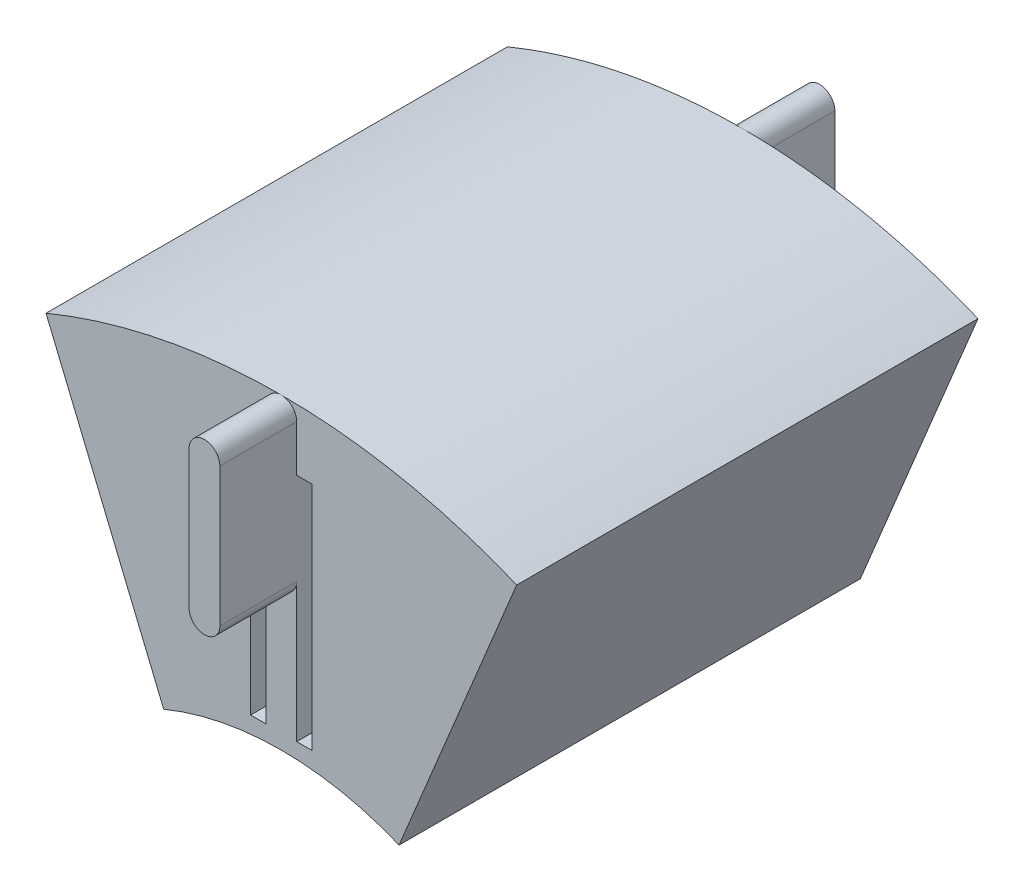
SolidWorks part; units mm, degrees
ref_plane "Ön Düzlem" through (0, 0, 0) normal (0, 0, 1) x (1, 0, 0)
ref_plane "Üst Düzlem" through (0, 0, 0) normal (0, 1, 0) x (1, 0, 0)
ref_plane "Sağ Düzlem" through (0, 0, 0) normal (1, 0, 0) x (0, 0, -1)
sketch "Sketch1" plane through (0, 0, 0) normal (0, 0, 1) x (1, 0, 0)
  line L0 (0, 0) -> (-0.7654, 1.8478) construction
  line L1 (-0.7654, 1.8478) -> (0.7654, 1.8478) construction
  line L2 (0.7654, 1.8478) -> (0, 0) construction
  line L3 (0, 0) -> (-1.5307, 3.6955) construction
  line L4 (0, 0) -> (1.5307, 3.6955) construction
  line L5 (-1.5307, 3.6955) -> (-0.7654, 1.8478)
  line L6 (0.7654, 1.8478) -> (1.5307, 3.6955)
  arc A1 (-1.5307, 3.6955) -> (1.5307, 3.6955) centre (0, 0) cw
  arc A2 (-0.7654, 1.8478) -> (0.7654, 1.8478) centre (0, 0) cw
  point P3 (0, 1.8478)
  dimension "D1" = 45
  dimension "D2" = 2
  dimension "D3" = 4
  dimension "D4" = 4
extrude "Boss-Extrude1" add sketch "Sketch1" along normal blind 3
sketch "Sketch2" plane through (0, 0, 3) normal (0, 0, 1) x (1, 0, 0)
  line L0 (0, 3) -> (0, 3.9) construction
  line L1 (-0.1, 3) -> (-0.1, 3.9)
  line L2 (0.1, 3) -> (0.1, 3.9)
  arc A1 (-0.1, 3) -> (0.1, 3) centre (0, 3) ccw
  arc A2 (0.1, 3.9) -> (-0.1, 3.9) centre (0, 3.9) ccw
  arc A3 (1.5307, 3.6955) -> (-1.5307, 3.6955) centre (0, 0) ccw construction
  point P7 (0, 3.45)
  point P12 (0, 0)
  dimension "D1" = 0.1
  dimension "D2" = 0.9
extrude "Boss-Extrude2" add sketch "Sketch2" along normal blind 0.5
sketch "Sketch3" plane through (0, 0, 0) normal (0, 0, -1) x (-1, 0, 0)
  line L0 (0, 3) -> (0, 3.9) construction
  line L1 (-0.1, 3) -> (-0.1, 3.9)
  line L2 (0.1, 3) -> (0.1, 3.9)
  arc A1 (-0.1, 3) -> (0.1, 3) centre (0, 3) ccw
  arc A2 (0.1, 3.9) -> (-0.1, 3.9) centre (0, 3.9) ccw
  arc A3 (1.5307, 3.6955) -> (-1.5307, 3.6955) centre (0, 0) ccw construction
  point P7 (0, 3.45)
  point P12 (0, 0)
  dimension "D1" = 0.1
  dimension "D2" = 0.9
extrude "Boss-Extrude3" add sketch "Sketch3" along normal blind 0.5
sketch "Sketch5" plane through (0.1, 0, 0) normal (1, 0, 0) x (0, 0, -1)
  line L0 (-3, 1.8478) -> (-3, 3.6955) construction
  line L2 (-3, 3.5978) -> (-3, 2.0978)
  line L3 (-3, 2.0978) -> (-1, 2.0978)
  line L6 (-3, 3.5978) -> (-1, 2.0978)
  dimension "D1" = 1.5
  dimension "D3" = 2
extrude "Cut-Extrude2" cut sketch "Sketch5" against normal blind 0.3 and the other way blind 0.1
sketch "Sketch9" plane through (0, 0, 3) normal (0, 0, 1) x (1, 0, 0)
  line L0 (0.2, 2.0978) -> (-0.2, 2.0978) construction
  line L1 (-0.1, 3.5978) -> (0.1, 3.5978)
  line L2 (-0.1, 3.5978) -> (-0.1, 2.0978)
  line L3 (-0.1, 2.0978) -> (0.1, 2.0978)
  line L4 (0.1, 3.5978) -> (0.1, 2.0978)
  line L5 (0.1, 3) -> (0.1, 3.9) construction
extrude "Boss-Extrude5" add sketch "Sketch9" against normal blind 3
